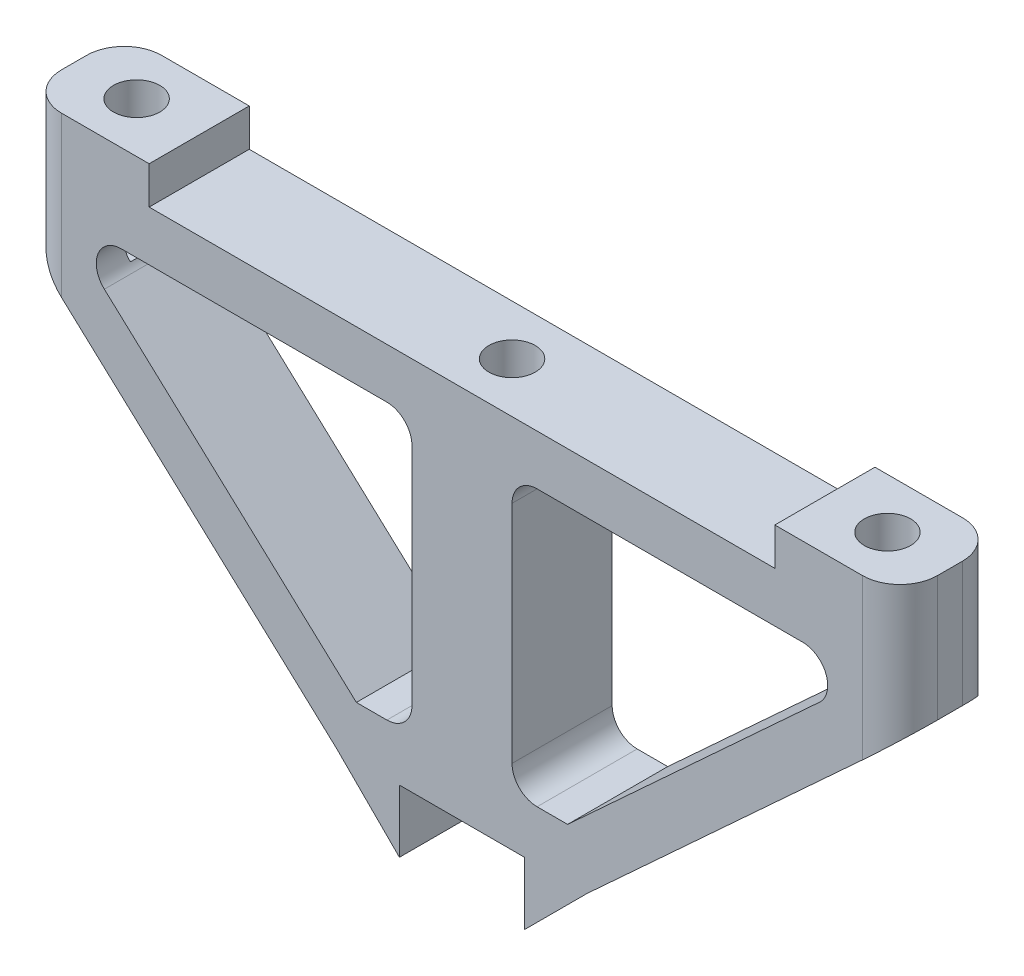
SolidWorks part; units mm, degrees
ref_plane "Front Plane" through (0, 0, 0) normal (0, 0, 1) x (1, 0, 0)
ref_plane "Top Plane" through (0, 0, 0) normal (0, 1, 0) x (1, 0, 0)
ref_plane "Right Plane" through (0, 0, 0) normal (1, 0, 0) x (0, 0, -1)
sketch "ｽｹｯﾁ1" plane through (0, 0, 0) normal (0, 0, 1) x (1, 0, 0)
  line L0 (0, 0) -> (-10, 0)
  line L1 (-10, 0) -> (-35, 23)
  line L2 (-35, 23) -> (-35, 30)
  line L3 (-35, 30) -> (0, 30)
  line L4 (0, 30) -> (0, 0)
  line L5 (-4, 26) -> (-4, 4)
  line L6 (-4, 4) -> (-8.4399, 4)
  line L7 (-8.4399, 4) -> (-32.3529, 26)
  line L8 (-32.3529, 26) -> (-4, 26)
  dimension "D1" = 35
  dimension "D2" = 7
  dimension "D3" = 4
  dimension "D4" = 0
  dimension "D5" = 4
  dimension "D6" = 4
  dimension "D7" = 10
  dimension "D8" = 30
  dimension "D9" = 4
extrude "ﾎﾞｽ - 押し出し1" add sketch "ｽｹｯﾁ1" along normal blind 8
mirror "ﾐﾗｰ1" about plane through (0, 30, 8) normal (-1, 0, 0) of "ﾎﾞｽ - 押し出し1"
fillet "ﾌｨﾚｯﾄ1" radius 2 6 edges at (32.3529, 26, 4) (4, 4, 4) (4, 26, 4) (-4, 4, 4) (-4, 26, 4) (-32.3529, 26, 4)
sketch "ｽｹｯﾁ2" plane through (0, 30, 0) normal (0, 1, 0) x (1, 0, 0)
  line L0 (35, -8) -> (35, 0) construction
  line L1 (35, 0) -> (-35, 0) construction
  line L2 (-35, -8) -> (-35, 0) construction
  circle A0 centre (0, -4) radius 1.85
  circle A1 centre (-30, -4) radius 1.85
  circle A2 centre (30, -4) radius 1.85
  point P12 (0, 0)
  dimension "D1" = 3.7
  dimension "D3" = 4
  dimension "D4" = 4
  dimension "D5" = 5
  dimension "D6" = 3.7
  dimension "D7" = 3.7
  dimension "D8" = 4
  dimension "D9" = 4
  dimension "D2" = 5
extrude "ｶｯﾄ - 押し出し1" cut sketch "ｽｹｯﾁ2" against normal blind 7
sketch "ｽｹｯﾁ3" plane through (0, 0, 0) normal (0, -1, 0) x (-1, 0, 0)
  line L0 (10, -8) -> (-10, -8) construction
  circle A0 centre (0, -4) radius 1.85
  dimension "D1" = 3.7
  dimension "D2" = 4
  dimension "D3" = 4
extrude "ｶｯﾄ - 押し出し2" cut sketch "ｽｹｯﾁ3" against normal blind 8
sketch "ｽｹｯﾁ4" plane through (0, 0, 0) normal (0, 0, -1) x (-1, 0, 0)
  line L0 (5, 0) -> (5, -5)
  line L1 (10, 0) -> (-10, 0) construction
  line L2 (5, -5) -> (10, 0)
  line L3 (10, 0) -> (5, 0)
  line L4 (-10, 0) -> (-5, 0)
  line L5 (-5, 0) -> (-5, -5)
  line L6 (-5, -5) -> (-10, 0)
  dimension "D1" = 10
  dimension "D2" = 5
  dimension "D3" = 5
  dimension "D4" = 5
extrude "ﾎﾞｽ - 押し出し2" add sketch "ｽｹｯﾁ4" against normal blind 8
sketch "ｽｹｯﾁ5" plane through (0, 30, 0) normal (0, 1, 0) x (1, 0, 0)
  line L0 (35, -8) -> (-35, -8) construction
  line L1 (35, 0) -> (25, 0)
  line L2 (35, 0) -> (35, -8)
  line L3 (35, -8) -> (25, -8)
  line L4 (25, 0) -> (25, -8)
  line L5 (35, 0) -> (-35, 0) construction
  line L6 (-35, -8) -> (-25, -8)
  line L7 (-35, -8) -> (-35, 0)
  line L8 (-35, 0) -> (-25, 0)
  line L9 (-25, -8) -> (-25, 0)
  circle A2 centre (30, -4) radius 1.85
  circle A3 centre (-30, -4) radius 1.85
  dimension "D2" = 3.7
  dimension "D3" = 3.7
  dimension "D1" = 10
  dimension "D4" = 10
extrude "ﾎﾞｽ - 押し出し3" add sketch "ｽｹｯﾁ5" along normal blind 3
fillet "ﾌｨﾚｯﾄ2" radius 3 4 edges at (-35, 28, 0) (-35, 28, 8) (35, 28, 0) (35, 28, 8)
